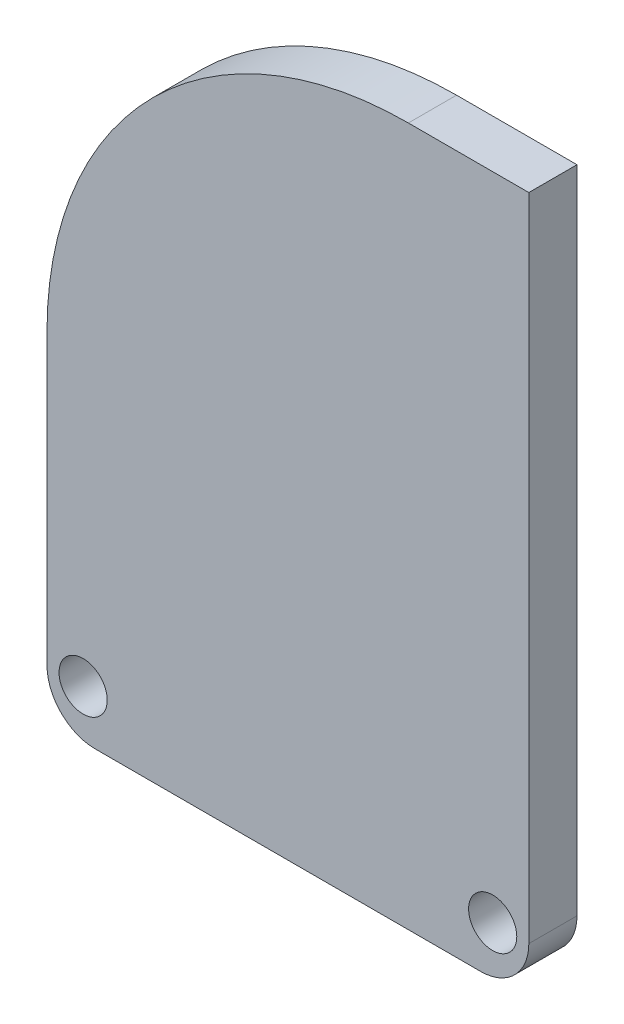
SolidWorks part; units mm, degrees
ref_plane "Front Plane" through (0, 0, 0) normal (0, 0, 1) x (1, 0, 0)
ref_plane "Top Plane" through (0, 0, 0) normal (0, 1, 0) x (1, 0, 0)
ref_plane "Right Plane" through (0, 0, 0) normal (1, 0, 0) x (0, 0, -1)
sketch "Sketch1" plane through (0, 0, 0) normal (0, 0, 1) x (1, 0, 0)
  line L0 (-18, -27) -> (-2, -27)
  line L1 (0, 0) -> (-5, 0)
  line L2 (0, 0) -> (0, -27)
  line L3 (-2, -29) -> (-18, -29)
  line L4 (-20, -15) -> (-20, -27)
  line L5 (-2, -27) -> (-1.5, -27)
  line L6 (-18, -27) -> (-18.5, -27)
  arc A0 (-5, 0) -> (-20, -15) centre (-5, -15) ccw
  arc A1 (0, -27) -> (-2, -29) centre (-2, -27) cw
  arc A2 (-18, -29) -> (-20, -27) centre (-18, -27) cw
  circle A3 centre (-18.5, -27) radius 1
  circle A4 centre (-1.5, -27) radius 1
  point P7 (-20, 0)
  point P10 (0, -29)
  dimension "D3" = 15
  dimension "D4" = 2
  dimension "D5" = 0.5
  dimension "D6" = 0.5
  dimension "D1" = 20
  dimension "D2" = 29
extrude "Boss-Extrude1" add sketch "Sketch1" along normal blind 2
